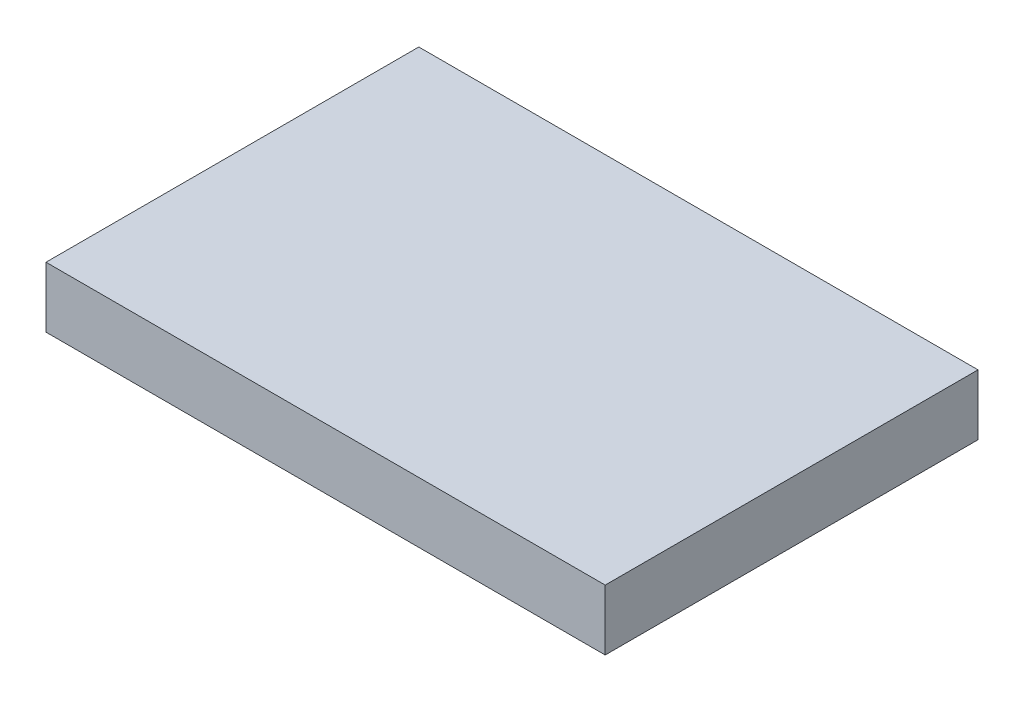
SolidWorks part; units mm, degrees
ref_plane "Front Plane" through (0, 0, 0) normal (0, 0, 1) x (1, 0, 0)
ref_plane "Top Plane" through (0, 0, 0) normal (0, 1, 0) x (1, 0, 0)
ref_plane "Right Plane" through (0, 0, 0) normal (1, 0, 0) x (0, 0, -1)
sketch "Sketch1" plane through (0, 0, 0) normal (0, 1, 0) x (1, 0, 0)
  line L1 (30, -20) -> (-30, -20)
  line L2 (30, -20) -> (30, 20)
  line L3 (30, 20) -> (-30, 20)
  line L4 (-30, -20) -> (-30, 20)
  line L5 (30, -20) -> (-30, 20) construction
  line L6 (30, 20) -> (-30, -20) construction
  point P0 (0, 0)
  dimension "D1" = 60
  dimension "D2" = 40
extrude "Boss-Extrude1" add sketch "Sketch1" along normal blind 6.5
